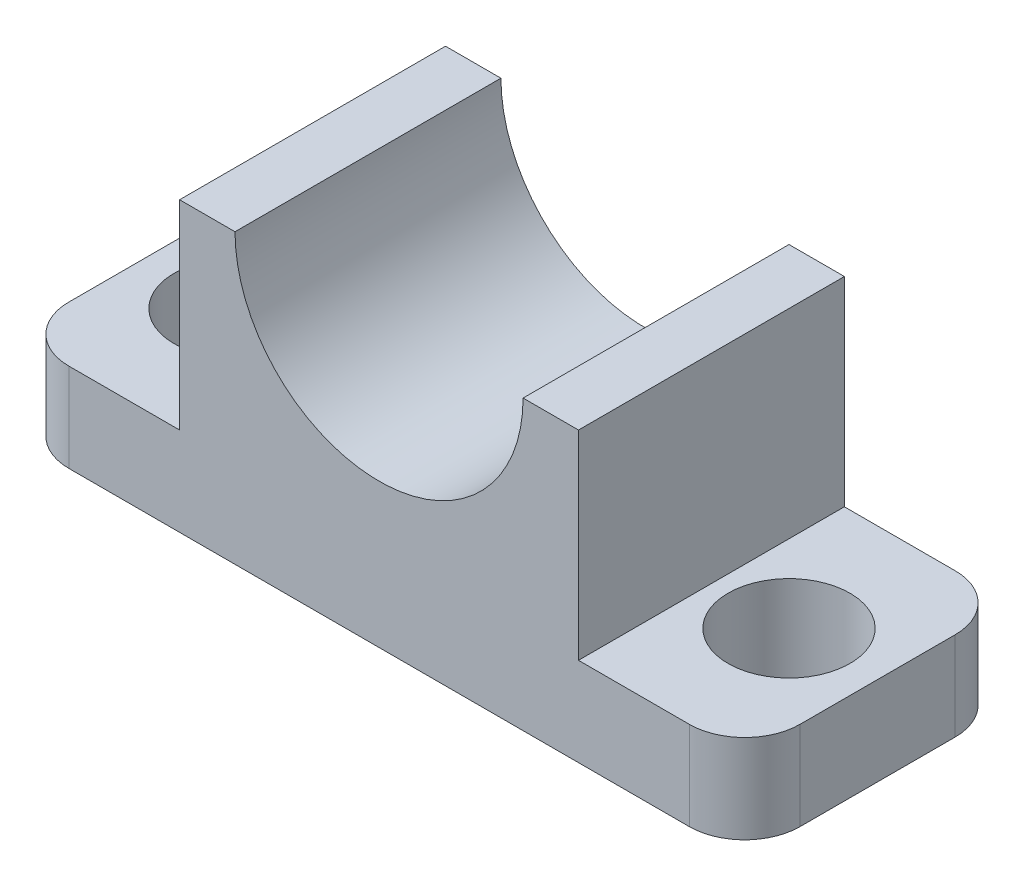
SolidWorks part; units mm, degrees
ref_plane "前视基准面" through (0, 0, 0) normal (0, 0, 1) x (1, 0, 0)
ref_plane "上视基准面" through (0, 0, 0) normal (0, 1, 0) x (1, 0, 0)
ref_plane "右视基准面" through (0, 0, 0) normal (1, 0, 0) x (0, 0, -1)
other "Configuration Table"
sketch "草图1" plane through (0, 0, 0) normal (0, 0, 1) x (1, 0, 0)
  line L0 (-33, 0) -> (33, 0)
  line L1 (33, 0) -> (33, 8)
  line L2 (33, 8) -> (18, 8)
  line L3 (18, 8) -> (18, 26)
  line L4 (18, 26) -> (13, 26)
  line L5 (0, -562.9354) -> (0, 27583.8341) construction
  line L6 (-18, 26) -> (-13, 26)
  line L7 (-18, 8) -> (-18, 26)
  line L8 (-33, 8) -> (-18, 8)
  line L9 (-33, 0) -> (-33, 8)
  arc A0 (-13, 26) -> (13, 26) centre (0, 26) ccw
  point P4 (0, 0)
  dimension "D2" = 13
  dimension "D1" = 36
  dimension "D3" = 26
  dimension "D4" = 8
  dimension "D5" = 66
extrude "凸台-拉伸1" add sketch "草图1" along normal mid plane 24
sketch "草图2" plane through (0, 8, 0) normal (0, 1, 0) x (1, 0, 0)
  line L0 (0, -1000) -> (0, 49000) construction
  line L1 (-1000, 0) -> (49000, 0) construction
  circle A0 centre (25, 0) radius 5.5
  circle A1 centre (-25, 0) radius 5.5
  dimension "D1" = 11
  dimension "D2" = 50
extrude "切除-拉伸1" cut sketch "草图2" against normal through all
fillet "圆角1" radius 5 4 edges at (-33, 4, 12) (-33, 4, -12) (33, 4, -12) (33, 4, 12)
